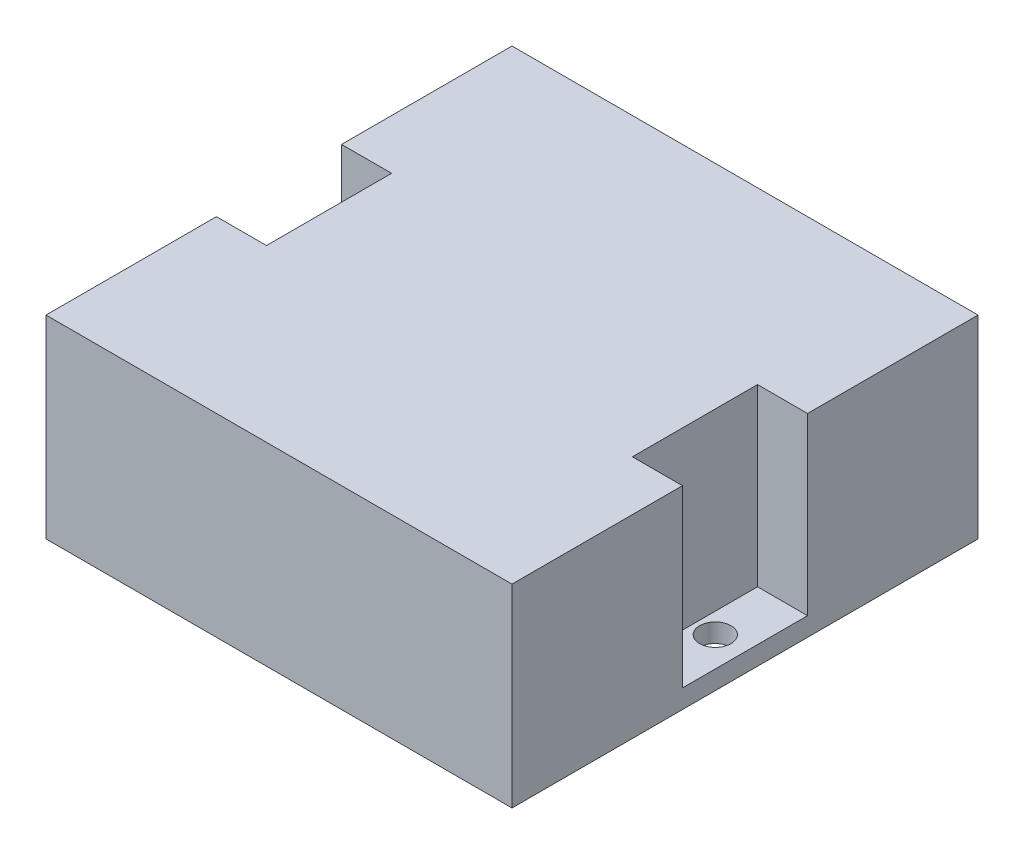
SolidWorks part; units mm, degrees
ref_plane "前视基准面" through (0, 0, 0) normal (0, 0, 1) x (1, 0, 0)
ref_plane "上视基准面" through (0, 0, 0) normal (0, 1, 0) x (1, 0, 0)
ref_plane "右视基准面" through (0, 0, 0) normal (1, 0, 0) x (0, 0, -1)
other "Configuration Table"
sketch "草图1" plane through (0, 0, 0) normal (0, 1, 0) x (1, 0, 0)
  line L1 (-37.25, -37.25) -> (37.25, -37.25)
  line L2 (-37.25, -37.25) -> (-37.25, 37.25)
  line L3 (-37.25, 37.25) -> (37.25, 37.25)
  line L4 (37.25, -37.25) -> (37.25, 37.25)
  line L5 (-37.25, -37.25) -> (37.25, 37.25) construction
  line L6 (-37.25, 37.25) -> (37.25, -37.25) construction
  point P0 (0, 0)
  dimension "D1" = 74.5
extrude "凸台-拉伸1" add sketch "草图1" along normal blind 31 contours L2 L1 L4 L3
sketch "草图2" plane through (0, 31, 0) normal (0, 1, 0) x (1, 0, 0)
  line L0 (-51.5663, 0) -> (44.7743, 0) construction
  line L1 (-37.25, -37.25) -> (-37.25, 37.25) construction
  line L2 (-29.25, 10) -> (-37.25, 10)
  line L3 (-29.25, 10) -> (-29.25, -10)
  line L4 (-29.25, -10) -> (-37.25, -10)
  line L5 (-37.25, 10) -> (-37.25, -10)
  line L6 (-29.25, 10) -> (-37.25, -10) construction
  line L7 (-29.25, -10) -> (-37.25, 10) construction
  line L8 (0, 45.9678) -> (0, -44.8861) construction
  line L9 (29.25, -10) -> (37.25, -10)
  line L10 (37.25, 10) -> (37.25, -10)
  line L11 (29.25, 10) -> (37.25, 10)
  line L12 (29.25, 10) -> (29.25, -10)
  point P2 (-33.25, 0)
  dimension "D1" = 8
  dimension "D2" = 20
extrude "切除-拉伸1" cut sketch "草图2" against normal blind 28
sketch "草图3" plane through (0, 3, 0) normal (0, 1, 0) x (1, 0, 0)
  line L0 (-50.3538, 0) -> (46.6337, 0) construction
  line L3 (0, 32.5311) -> (0, -43.0095) construction
  circle A0 centre (-32.5, 0) radius 2.5
  circle A1 centre (32.5, 0) radius 2.5
  dimension "D1" = 5
  dimension "D2" = 65
extrude "切除-拉伸2" cut sketch "草图3" against normal through all
